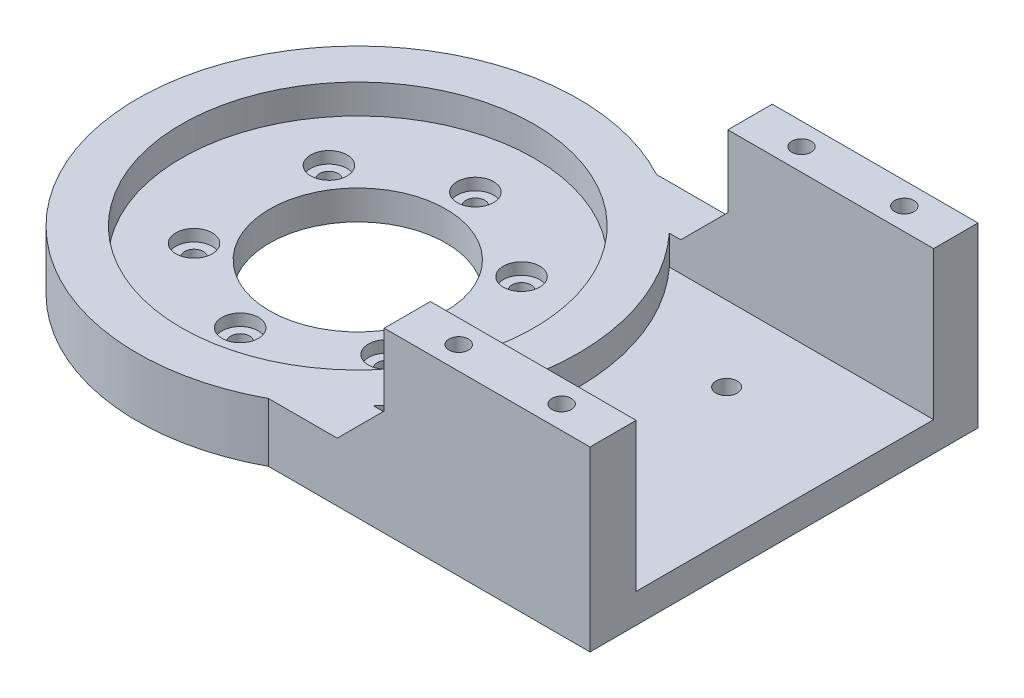
SolidWorks part; units mm, degrees
ref_plane "Front Plane" through (0, 0, 0) normal (0, 0, 1) x (1, 0, 0)
ref_plane "Top Plane" through (0, 0, 0) normal (0, 1, 0) x (1, 0, 0)
ref_plane "Right Plane" through (0, 0, 0) normal (1, 0, 0) x (0, 0, -1)
sketch "Sketch1" plane through (0, 0, 0) normal (0, 1, 0) x (1, 0, 0)
  circle A0 centre (0, 0) radius 15
  circle A1 centre (0, 0) radius 37.5
  dimension "D1" = 30
  dimension "D2" = 75
extrude "Boss-Extrude2" add sketch "Sketch1" along normal blind 5
sketch "Sketch3" plane through (0, 5, 0) normal (0, 1, 0) x (1, 0, 0)
  circle A0 centre (0, 0) radius 30
  circle A1 centre (0, 0) radius 37.5
  dimension "D1" = 60
extrude "Boss-Extrude3" add sketch "Sketch3" along normal blind 5
sketch "Sketch4" plane through (0, 5, 0) normal (0, 1, 0) x (1, 0, 0)
  line L0 (0, 0) -> (0, 20) construction
  line L1 (0, 0) -> (-16.383, 11.4715) construction
  line L2 (0, 0) -> (16.383, 11.4715) construction
  line L3 (0, 0) -> (-7.7431, 0) construction
  circle A0 centre (0, 20) radius 1.6
  circle A1 centre (-16.383, 11.4715) radius 1.6
  circle A2 centre (16.383, 11.4715) radius 1.6
  circle A3 centre (16.383, -11.4715) radius 1.6
  circle A4 centre (0, -20) radius 1.6
  circle A5 centre (-16.383, -11.4715) radius 1.6
  dimension "D2" = 3.2
  dimension "D1" = 20
  dimension "D3" = 55
  dimension "D4" = 20
  dimension "D5" = 55
  dimension "D6" = 20
extrude "Cut-Extrude1" cut sketch "Sketch4" against normal blind 5
sketch "Sketch5" plane through (0, 5, 0) normal (0, 1, 0) x (1, 0, 0)
  line L0 (0, 0) -> (-6.2782, 0) construction
  circle A0 centre (0, 20) radius 3.1
  circle A1 centre (-16.383, 11.4715) radius 3.1
  circle A2 centre (16.383, 11.4715) radius 3.1
  circle A3 centre (16.383, -11.4715) radius 3.1
  circle A4 centre (-16.383, -11.4715) radius 3.1
  circle A5 centre (0, -20) radius 3.1
  dimension "D1" = 6.2
extrude "Cut-Extrude2" cut sketch "Sketch5" against normal blind 2
sketch "Sketch6" plane through (0, 5, 0) normal (0, 1, 0) x (1, 0, 0)
  line L1 (-15, 0) -> (15, 0) construction
  circle A1 centre (0, 0) radius 15 construction
ref_plane "Plane1" through (37.5, 0, 0) normal (1, 0, 0) x (0, 0, -1)
sketch "Sketch8" plane through (37.5, 0, 0) normal (1, 0, 0) x (0, 0, -1)
  line L0 (0, 10) -> (0, 0) construction
  line L1 (37.5, 10) -> (-37.5, 10) construction
  line L2 (0, 5) -> (-25.15, 5) construction
  line L3 (0, 5) -> (25.45, 5) construction
  line L4 (-10.1453, 5) -> (-10.1453, 0) construction
  line L5 (-37.5, 0) -> (37.5, 0) construction
  line L6 (33, 5) -> (-33, 5) construction
  line L7 (33, 10) -> (33, 0)
  line L8 (-33, 0) -> (-33, 10)
  line L9 (30, 10) -> (-30, 10) construction
  line L10 (-33, 10) -> (-25.15, 10)
  line L11 (-25.15, 10) -> (-25.15, 5)
  line L12 (-25.15, 5) -> (25.45, 5)
  line L13 (25.45, 5) -> (25.45, 10)
  line L14 (25.45, 10) -> (33, 10)
  line L15 (-33, 0) -> (33, 0)
  dimension "D1" = 25.15
  dimension "D2" = 33
extrude "Boss-Extrude4" add sketch "Sketch8" along normal blind 35 and the other way up to surface other way up to face at (0, 0, 37.5)
sketch "Sketch9" plane through (0, 10, 0) normal (0, 1, 0) x (1, 0, 0)
  line L0 (37.5, -5.5) -> (37.5, 5.5) construction
  line L1 (37.5, -33) -> (72.5, -33)
  line L2 (37.5, -33) -> (37.5, -25.15)
  line L3 (37.5, -25.15) -> (72.5, -25.15)
  line L4 (72.5, -33) -> (72.5, -25.15)
  line L5 (72.5, -33) -> (17.8115, -33) construction
  line L6 (72.5, 25.45) -> (27.5417, 25.45) construction
  line L7 (72.5, 33) -> (37.5, 33)
  line L8 (72.5, 33) -> (72.5, 25.45)
  line L9 (72.5, 25.45) -> (37.5, 25.45)
  line L10 (37.5, 33) -> (37.5, 25.45)
extrude "Boss-Extrude5" add sketch "Sketch9" along normal blind 20.2
chamfer "Chamfer1" distance 8 angle 45 2 edges at (37.5, 10, -29.225) (37.5, 10, 29.075)
sketch "Sketch11" plane through (0, 30.2, 0) normal (0, 1, 0) x (1, 0, 0)
  line L0 (72.5, 29.225) -> (63.75, 29.225) construction
  line L1 (72.5, 25.45) -> (72.5, 33) construction
  line L2 (72.5, -29.075) -> (63.75, -29.075) construction
  line L3 (72.5, -33) -> (72.5, -25.15) construction
  line L4 (37.5, -29.075) -> (46.25, -29.075) construction
  line L5 (37.5, -5.5) -> (37.5, 5.5) construction
  line L6 (37.5, 29.225) -> (46.25, 29.225) construction
  line L7 (72.5, 33) -> (37.5, 33) construction
  circle A0 centre (46.25, 29.225) radius 1.65
  circle A1 centre (63.75, 29.225) radius 1.65
  circle A2 centre (63.75, -29.075) radius 1.65
  circle A3 centre (46.25, -29.075) radius 1.65
  dimension "D3" = 3.3
  dimension "D1" = 8.75
  dimension "D2" = 8.75
  dimension "D4" = 3.775
extrude "Cut-Extrude3" cut sketch "Sketch11" against normal through all
sketch "Sketch12" plane through (0, 0, 0) normal (0, -1, 0) x (1, 0, 0)
  circle A0 centre (46.25, 29.075) radius 3.1
  circle A1 centre (63.75, 29.075) radius 3.1
  circle A2 centre (63.75, -29.225) radius 3.1
  circle A3 centre (46.25, -29.225) radius 3.1
  dimension "D1" = 6.2
extrude "Cut-Extrude4" cut sketch "Sketch12" against normal blind 2.5
sketch "Sketch15" plane through (0, 5, 0) normal (0, 1, 0) x (1, 0, 0)
  line L1 (72.5, -25.15) -> (27.816, -25.15) construction
  line L3 (50.0898, 0) -> (37.5, 0) construction
  line L4 (37.5, -5.5) -> (37.5, 5.5) construction
  line L5 (43.7949, 0) -> (43.7949, 25.45) construction
  line L6 (37.5, 25.45) -> (72.5, 25.45) construction
  line L7 (43.7949, 0) -> (43.7949, -25.15) construction
  circle A1 centre (50.0898, 12.65) radius 1.8
  circle A2 centre (50.0898, -12.65) radius 1.8
  dimension "D1" = 3.6
extrude "Cut-Extrude5" cut sketch "Sketch15" against normal blind 10
